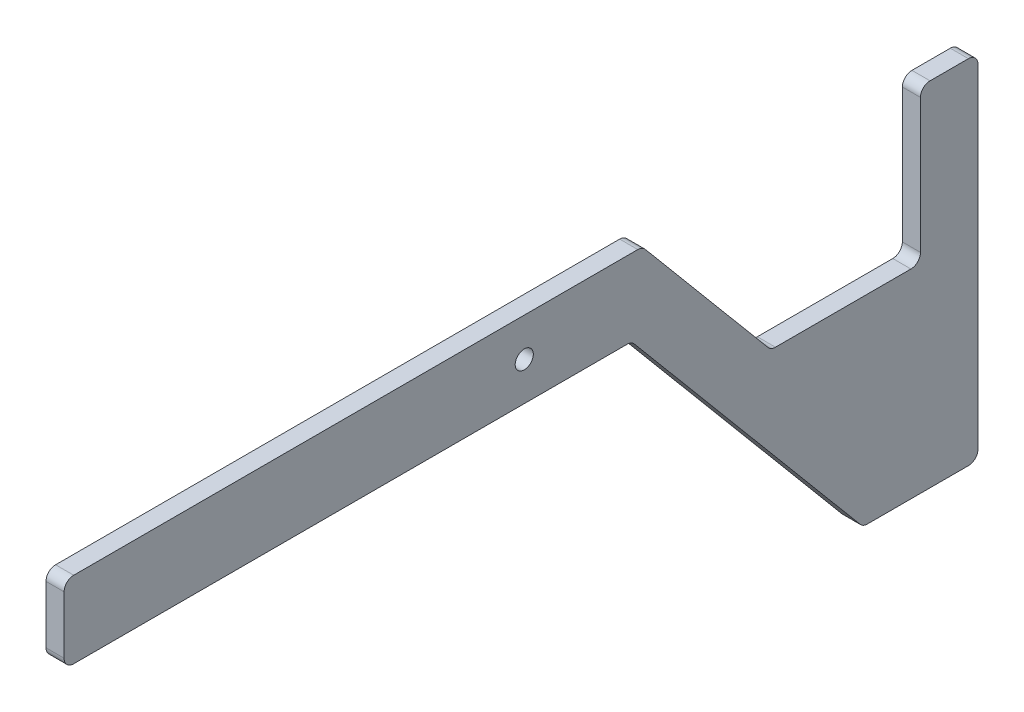
SolidWorks part; units mm, degrees
ref_plane "Front Plane" through (0, 0, 0) normal (0, 0, 1) x (1, 0, 0)
ref_plane "Top Plane" through (0, 0, 0) normal (0, 1, 0) x (1, 0, 0)
ref_plane "Right Plane" through (0, 0, 0) normal (1, 0, 0) x (0, 0, -1)
sketch "Sketch1" plane through (0, 0, 0) normal (1, 0, 0) x (0, 0, -1)
  line L0 (-75.6681, 16.4863) -> (-75.6681, 29.1863)
  line L1 (75.6681, -29.1863) -> (-75.6681, -29.1863) construction
  line L2 (75.6681, -29.1863) -> (75.6681, 29.1863) construction
  line L3 (75.6681, 29.1863) -> (66.1431, 29.1863) construction
  line L4 (-75.6681, -29.1863) -> (-75.6681, 29.1863) construction
  line L5 (75.6681, -29.1863) -> (-75.6681, 29.1863) construction
  line L6 (75.6681, 29.1863) -> (-75.6681, -29.1863) construction
  line L7 (-75.6681, 29.1863) -> (20.0717, 29.1863)
  line L8 (75.6681, 29.1863) -> (75.6681, -29.1863)
  line L9 (18.2942, 16.4863) -> (56.6181, -29.1863)
  line L10 (18.2942, 16.4863) -> (-75.6681, 16.4863)
  line L11 (56.6181, -29.1863) -> (75.6681, -29.1863)
  line L12 (18.2942, 16.4863) -> (7.6377, 29.1863) construction
  line L13 (20.0717, 29.1863) -> (41.3848, 3.7863)
  line L14 (41.3848, 3.7863) -> (66.1431, 3.7863)
  line L15 (66.1431, 3.7863) -> (66.1431, 29.1863)
  line L16 (66.1431, 29.1863) -> (20.0717, 29.1863) construction
  line L17 (20.0717, 29.1863) -> (-75.6681, 29.1863) construction
  line L18 (20.0717, 29.1863) -> (66.1431, 29.1863) construction
  line L19 (66.1431, 29.1863) -> (75.6681, 29.1863)
  circle A0 centre (0.5319, 22.8363) radius 1.5
  point P0 (0, 0)
  dimension "D5" = 3
  dimension "D2" = 50
  dimension "D3" = 76.2
  dimension "D4" = 12.7
  dimension "D6" = 6.35
  dimension "D7" = 19.05
  dimension "D8" = 9.525
  dimension "D9" = 76.2
  dimension "D10" = 9.525
  dimension "D11" = 9.525
  dimension "D12" = 25.4
extrude "Boss-Extrude1" add sketch "Sketch1" along normal mid plane 3
fillet "Fillet1" radius 1.5875 10 edges at (0, 29.1863, -20.0717) (0, 3.7863, -41.3848) (0, 3.7863, -66.1431) (0, 29.1863, -66.1431) (0, 29.1863, -75.6681) (0, -29.1863, -75.6681) (0, -29.1863, -56.6181) (0, 16.4863, 75.6681) (0, 29.1863, 75.6681) (0, 16.4863, -18.2942)
